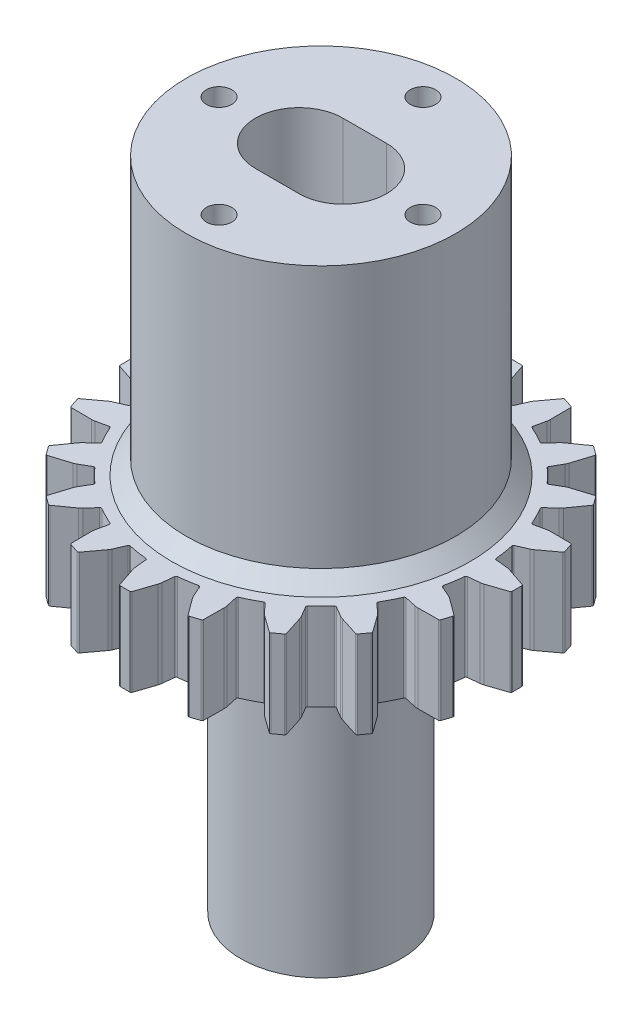
SolidWorks part; units mm, degrees
ref_plane "Front Plane" through (0, 0, 0) normal (0, 0, 1) x (1, 0, 0)
ref_plane "Top Plane" through (0, 0, 0) normal (0, 1, 0) x (1, 0, 0)
ref_plane "Right Plane" through (0, 0, 0) normal (1, 0, 0) x (0, 0, -1)
sketch "Sketch1" plane through (0, 0, 0) normal (0, 1, 0) x (1, 0, 0)
  line L0 (0, 23.8701) -> (0, -17.0658) construction
  line L1 (-0.9918, 11.0363) -> (-0.9111, 11.8435)
  line L2 (-0.8647, 12.0602) -> (-0.4228, 13.3861)
  line L3 (-0.3279, 13.4545) -> (0.3279, 13.4545)
  line L4 (0.4228, 13.3861) -> (0.8647, 12.0602)
  line L5 (0.9111, 11.8435) -> (0.9918, 11.0363)
  line L6 (2.4671, 10.8026) -> (2.7933, 11.5454)
  line L7 (2.9044, 11.7372) -> (3.7344, 12.8616)
  line L8 (3.8458, 12.8973) -> (4.4695, 12.6946)
  line L9 (4.5386, 12.6003) -> (4.5492, 11.2027)
  line L10 (4.5263, 10.9823) -> (4.3537, 10.1896)
  line L11 (5.6846, 9.5115) -> (6.2243, 10.1171)
  line L12 (6.3892, 10.2652) -> (7.5261, 11.0781)
  line L13 (7.643, 11.0776) -> (8.1736, 10.6921)
  line L14 (8.2102, 10.5811) -> (7.7884, 9.2486)
  line L15 (7.6985, 9.0461) -> (7.2894, 8.3456)
  line L16 (8.3456, 7.2894) -> (9.0461, 7.6985)
  line L17 (9.2486, 7.7884) -> (10.5811, 8.2102)
  line L18 (10.6921, 8.1736) -> (11.0776, 7.643)
  line L19 (11.0781, 7.5261) -> (10.2652, 6.3892)
  line L20 (10.1171, 6.2243) -> (9.5115, 5.6846)
  line L21 (10.1896, 4.3537) -> (10.9823, 4.5263)
  line L22 (11.2027, 4.5492) -> (12.6003, 4.5386)
  line L23 (12.6946, 4.4695) -> (12.8973, 3.8458)
  line L24 (12.8616, 3.7344) -> (11.7372, 2.9044)
  line L25 (11.5454, 2.7933) -> (10.8026, 2.4671)
  line L26 (11.0363, 0.9918) -> (11.8435, 0.9111)
  line L27 (12.0602, 0.8647) -> (13.3861, 0.4228)
  line L28 (13.4545, 0.3279) -> (13.4545, -0.3279)
  line L29 (13.3861, -0.4228) -> (12.0602, -0.8647)
  line L30 (11.8435, -0.9111) -> (11.0363, -0.9918)
  line L31 (10.8026, -2.4671) -> (11.5454, -2.7933)
  line L32 (11.7372, -2.9044) -> (12.8616, -3.7344)
  line L33 (12.8973, -3.8458) -> (12.6946, -4.4695)
  line L34 (12.6003, -4.5386) -> (11.2027, -4.5492)
  line L35 (10.9823, -4.5263) -> (10.1896, -4.3537)
  line L36 (9.5115, -5.6846) -> (10.1171, -6.2243)
  line L37 (10.2652, -6.3892) -> (11.0781, -7.5261)
  line L38 (11.0776, -7.643) -> (10.6921, -8.1736)
  line L39 (10.5811, -8.2102) -> (9.2486, -7.7884)
  line L40 (9.0461, -7.6985) -> (8.3456, -7.2894)
  line L41 (7.2894, -8.3456) -> (7.6985, -9.0461)
  line L42 (7.7884, -9.2486) -> (8.2102, -10.5811)
  line L43 (8.1736, -10.6921) -> (7.643, -11.0776)
  line L44 (7.5261, -11.0781) -> (6.3892, -10.2652)
  line L45 (6.2243, -10.1171) -> (5.6846, -9.5115)
  line L46 (4.3537, -10.1896) -> (4.5263, -10.9823)
  line L47 (4.5492, -11.2027) -> (4.5386, -12.6003)
  line L48 (4.4695, -12.6946) -> (3.8458, -12.8973)
  line L49 (3.7344, -12.8616) -> (2.9044, -11.7372)
  line L50 (2.7933, -11.5454) -> (2.4671, -10.8026)
  line L51 (0.9918, -11.0363) -> (0.9111, -11.8435)
  line L52 (0.8647, -12.0602) -> (0.4228, -13.3861)
  line L53 (0.3279, -13.4545) -> (-0.3279, -13.4545)
  line L54 (-0.4228, -13.3861) -> (-0.8647, -12.0602)
  line L55 (-0.9111, -11.8435) -> (-0.9918, -11.0363)
  line L56 (-2.4671, -10.8026) -> (-2.7933, -11.5454)
  line L57 (-2.9044, -11.7372) -> (-3.7344, -12.8616)
  line L58 (-3.8458, -12.8973) -> (-4.4695, -12.6946)
  line L59 (-4.5386, -12.6003) -> (-4.5492, -11.2027)
  line L60 (-4.5263, -10.9823) -> (-4.3537, -10.1896)
  line L61 (-5.6846, -9.5115) -> (-6.2243, -10.1171)
  line L62 (-6.3892, -10.2652) -> (-7.5261, -11.0781)
  line L63 (-7.643, -11.0776) -> (-8.1736, -10.6921)
  line L64 (-8.2102, -10.5811) -> (-7.7884, -9.2486)
  line L65 (-7.6985, -9.0461) -> (-7.2894, -8.3456)
  line L66 (-8.3456, -7.2894) -> (-9.0461, -7.6985)
  line L67 (-9.2486, -7.7884) -> (-10.5811, -8.2102)
  line L68 (-10.6921, -8.1736) -> (-11.0776, -7.643)
  line L69 (-11.0781, -7.5261) -> (-10.2652, -6.3892)
  line L70 (-10.1171, -6.2243) -> (-9.5115, -5.6846)
  line L71 (-10.1896, -4.3537) -> (-10.9823, -4.5263)
  line L72 (-11.2027, -4.5492) -> (-12.6003, -4.5386)
  line L73 (-12.6946, -4.4695) -> (-12.8973, -3.8458)
  line L74 (-12.8616, -3.7344) -> (-11.7372, -2.9044)
  line L75 (-11.5454, -2.7933) -> (-10.8026, -2.4671)
  line L76 (-11.0363, -0.9918) -> (-11.8435, -0.9111)
  line L77 (-12.0602, -0.8647) -> (-13.3861, -0.4228)
  line L78 (-13.4545, -0.3279) -> (-13.4545, 0.3279)
  line L79 (-13.3861, 0.4228) -> (-12.0602, 0.8647)
  line L80 (-11.8435, 0.9111) -> (-11.0363, 0.9918)
  line L81 (-10.8026, 2.4671) -> (-11.5454, 2.7933)
  line L82 (-11.7372, 2.9044) -> (-12.8616, 3.7344)
  line L83 (-12.8973, 3.8458) -> (-12.6946, 4.4695)
  line L84 (-12.6003, 4.5386) -> (-11.2027, 4.5492)
  line L85 (-10.9823, 4.5263) -> (-10.1896, 4.3537)
  line L86 (-9.5115, 5.6846) -> (-10.1171, 6.2243)
  line L87 (-10.2652, 6.3892) -> (-11.0781, 7.5261)
  line L88 (-11.0776, 7.643) -> (-10.6921, 8.1736)
  line L89 (-10.5811, 8.2102) -> (-9.2486, 7.7884)
  line L90 (-9.0461, 7.6985) -> (-8.3456, 7.2894)
  line L91 (-7.2894, 8.3456) -> (-7.6985, 9.0461)
  line L92 (-7.7884, 9.2486) -> (-8.2102, 10.5811)
  line L93 (-8.1736, 10.6921) -> (-7.643, 11.0776)
  line L94 (-7.5261, 11.0781) -> (-6.3892, 10.2652)
  line L95 (-6.2243, 10.1171) -> (-5.6846, 9.5115)
  line L96 (-4.3537, 10.1896) -> (-4.5263, 10.9823)
  line L97 (-4.5492, 11.2027) -> (-4.5386, 12.6003)
  line L98 (-4.4695, 12.6946) -> (-3.8458, 12.8973)
  line L99 (-3.7344, 12.8616) -> (-2.9044, 11.7372)
  line L100 (-2.7933, 11.5454) -> (-2.4671, 10.8026)
  arc A0 (-1.0815, 10.9467) -> (-2.3542, 10.7451) centre (0, 0) ccw
  arc A1 (0.8647, 12.0602) -> (0.9111, 11.8435) centre (-0.0839, 11.744) cw
  arc A2 (-0.9111, 11.8435) -> (-0.8647, 12.0602) centre (0.0839, 11.744) cw
  arc A3 (0.3279, 13.4545) -> (0.4228, 13.3861) centre (0.3279, 13.3545) cw
  arc A4 (-0.4228, 13.3861) -> (-0.3279, 13.4545) centre (-0.3279, 13.3545) cw
  arc A5 (0.9918, 11.0363) -> (1.0815, 10.9467) centre (1.0913, 11.0462) ccw
  arc A6 (-0.9918, 11.0363) -> (-1.0815, 10.9467) centre (-1.0913, 11.0462) cw
  arc A7 (2.4671, 10.8026) -> (2.3542, 10.7451) centre (2.3756, 10.8428) cw
  arc A8 (2.7933, 11.5454) -> (2.9044, 11.7372) centre (3.7089, 11.1433) cw
  arc A9 (3.7344, 12.8616) -> (3.8458, 12.8973) centre (3.8149, 12.8022) cw
  arc A10 (4.4695, 12.6946) -> (4.5386, 12.6003) centre (4.4386, 12.5995) cw
  arc A11 (4.5492, 11.2027) -> (4.5263, 10.9823) centre (3.5493, 11.1951) cw
  arc A12 (4.3537, 10.1896) -> (4.4113, 10.0767) centre (4.4514, 10.1683) ccw
  arc A13 (5.6846, 9.5115) -> (5.5594, 9.4918) centre (5.6099, 9.578) cw
  arc A14 (6.2243, 10.1171) -> (6.3892, 10.2652) centre (6.9709, 9.4518) cw
  arc A15 (7.5261, 11.0781) -> (7.643, 11.0776) centre (7.5843, 10.9967) cw
  arc A16 (8.1736, 10.6921) -> (8.2102, 10.5811) centre (8.1148, 10.6112) cw
  arc A17 (7.7884, 9.2486) -> (7.6985, 9.0461) centre (6.835, 9.5504) cw
  arc A18 (7.2894, 8.3456) -> (7.3093, 8.2204) centre (7.3757, 8.2951) ccw
  arc A19 (8.3456, 7.2894) -> (8.2204, 7.3093) centre (8.2951, 7.3757) cw
  arc A20 (9.0461, 7.6985) -> (9.2486, 7.7884) centre (9.5504, 6.835) cw
  arc A21 (10.5811, 8.2102) -> (10.6921, 8.1736) centre (10.6112, 8.1148) cw
  arc A22 (11.0776, 7.643) -> (11.0781, 7.5261) centre (10.9967, 7.5843) cw
  arc A23 (10.2652, 6.3892) -> (10.1171, 6.2243) centre (9.4518, 6.9709) cw
  arc A24 (9.5115, 5.6846) -> (9.4918, 5.5594) centre (9.578, 5.6099) ccw
  arc A25 (10.1896, 4.3537) -> (10.0767, 4.4113) centre (10.1683, 4.4514) cw
  arc A26 (10.9823, 4.5263) -> (11.2027, 4.5492) centre (11.1951, 3.5493) cw
  arc A27 (12.6003, 4.5386) -> (12.6946, 4.4695) centre (12.5995, 4.4386) cw
  arc A28 (12.8973, 3.8458) -> (12.8616, 3.7344) centre (12.8022, 3.8149) cw
  arc A29 (11.7372, 2.9044) -> (11.5454, 2.7933) centre (11.1433, 3.7089) cw
  arc A30 (10.8026, 2.4671) -> (10.7451, 2.3542) centre (10.8428, 2.3756) ccw
  arc A31 (11.0363, 0.9918) -> (10.9467, 1.0815) centre (11.0462, 1.0913) cw
  arc A32 (11.8435, 0.9111) -> (12.0602, 0.8647) centre (11.744, -0.0839) cw
  arc A33 (13.3861, 0.4228) -> (13.4545, 0.3279) centre (13.3545, 0.3279) cw
  arc A34 (13.4545, -0.3279) -> (13.3861, -0.4228) centre (13.3545, -0.3279) cw
  arc A35 (12.0602, -0.8647) -> (11.8435, -0.9111) centre (11.744, 0.0839) cw
  arc A36 (11.0363, -0.9918) -> (10.9467, -1.0815) centre (11.0462, -1.0913) ccw
  arc A37 (10.8026, -2.4671) -> (10.7451, -2.3542) centre (10.8428, -2.3756) cw
  arc A38 (11.5454, -2.7933) -> (11.7372, -2.9044) centre (11.1433, -3.7089) cw
  arc A39 (12.8616, -3.7344) -> (12.8973, -3.8458) centre (12.8022, -3.8149) cw
  arc A40 (12.6946, -4.4695) -> (12.6003, -4.5386) centre (12.5995, -4.4386) cw
  arc A41 (11.2027, -4.5492) -> (10.9823, -4.5263) centre (11.1951, -3.5493) cw
  arc A42 (10.1896, -4.3537) -> (10.0767, -4.4113) centre (10.1683, -4.4514) ccw
  arc A43 (9.5115, -5.6846) -> (9.4918, -5.5594) centre (9.578, -5.6099) cw
  arc A44 (10.1171, -6.2243) -> (10.2652, -6.3892) centre (9.4518, -6.9709) cw
  arc A45 (11.0781, -7.5261) -> (11.0776, -7.643) centre (10.9967, -7.5843) cw
  arc A46 (10.6921, -8.1736) -> (10.5811, -8.2102) centre (10.6112, -8.1148) cw
  arc A47 (9.2486, -7.7884) -> (9.0461, -7.6985) centre (9.5504, -6.835) cw
  arc A48 (8.3456, -7.2894) -> (8.2204, -7.3093) centre (8.2951, -7.3757) ccw
  arc A49 (7.2894, -8.3456) -> (7.3093, -8.2204) centre (7.3757, -8.2951) cw
  arc A50 (7.6985, -9.0461) -> (7.7884, -9.2486) centre (6.835, -9.5504) cw
  arc A51 (8.2102, -10.5811) -> (8.1736, -10.6921) centre (8.1148, -10.6112) cw
  arc A52 (7.643, -11.0776) -> (7.5261, -11.0781) centre (7.5843, -10.9967) cw
  arc A53 (6.3892, -10.2652) -> (6.2243, -10.1171) centre (6.9709, -9.4518) cw
  arc A54 (5.6846, -9.5115) -> (5.5594, -9.4918) centre (5.6099, -9.578) ccw
  arc A55 (4.3537, -10.1896) -> (4.4113, -10.0767) centre (4.4514, -10.1683) cw
  arc A56 (4.5263, -10.9823) -> (4.5492, -11.2027) centre (3.5493, -11.1951) cw
  arc A57 (4.5386, -12.6003) -> (4.4695, -12.6946) centre (4.4386, -12.5995) cw
  arc A58 (3.8458, -12.8973) -> (3.7344, -12.8616) centre (3.8149, -12.8022) cw
  arc A59 (2.9044, -11.7372) -> (2.7933, -11.5454) centre (3.7089, -11.1433) cw
  arc A60 (2.4671, -10.8026) -> (2.3542, -10.7451) centre (2.3756, -10.8428) ccw
  arc A61 (0.9918, -11.0363) -> (1.0815, -10.9467) centre (1.0913, -11.0462) cw
  arc A62 (0.9111, -11.8435) -> (0.8647, -12.0602) centre (-0.0839, -11.744) cw
  arc A63 (0.4228, -13.3861) -> (0.3279, -13.4545) centre (0.3279, -13.3545) cw
  arc A64 (-0.3279, -13.4545) -> (-0.4228, -13.3861) centre (-0.3279, -13.3545) cw
  arc A65 (-0.8647, -12.0602) -> (-0.9111, -11.8435) centre (0.0839, -11.744) cw
  arc A66 (-0.9918, -11.0363) -> (-1.0815, -10.9467) centre (-1.0913, -11.0462) ccw
  arc A67 (-2.4671, -10.8026) -> (-2.3542, -10.7451) centre (-2.3756, -10.8428) cw
  arc A68 (-2.7933, -11.5454) -> (-2.9044, -11.7372) centre (-3.7089, -11.1433) cw
  arc A69 (-3.7344, -12.8616) -> (-3.8458, -12.8973) centre (-3.8149, -12.8022) cw
  arc A70 (-4.4695, -12.6946) -> (-4.5386, -12.6003) centre (-4.4386, -12.5995) cw
  arc A71 (-4.5492, -11.2027) -> (-4.5263, -10.9823) centre (-3.5493, -11.1951) cw
  arc A72 (-4.3537, -10.1896) -> (-4.4113, -10.0767) centre (-4.4514, -10.1683) ccw
  arc A73 (-5.6846, -9.5115) -> (-5.5594, -9.4918) centre (-5.6099, -9.578) cw
  arc A74 (-6.2243, -10.1171) -> (-6.3892, -10.2652) centre (-6.9709, -9.4518) cw
  arc A75 (-7.5261, -11.0781) -> (-7.643, -11.0776) centre (-7.5843, -10.9967) cw
  arc A76 (-8.1736, -10.6921) -> (-8.2102, -10.5811) centre (-8.1148, -10.6112) cw
  arc A77 (-7.7884, -9.2486) -> (-7.6985, -9.0461) centre (-6.835, -9.5504) cw
  arc A78 (-7.2894, -8.3456) -> (-7.3093, -8.2204) centre (-7.3757, -8.2951) ccw
  arc A79 (-8.3456, -7.2894) -> (-8.2204, -7.3093) centre (-8.2951, -7.3757) cw
  arc A80 (-9.0461, -7.6985) -> (-9.2486, -7.7884) centre (-9.5504, -6.835) cw
  arc A81 (-10.5811, -8.2102) -> (-10.6921, -8.1736) centre (-10.6112, -8.1148) cw
  arc A82 (-11.0776, -7.643) -> (-11.0781, -7.5261) centre (-10.9967, -7.5843) cw
  arc A83 (-10.2652, -6.3892) -> (-10.1171, -6.2243) centre (-9.4518, -6.9709) cw
  arc A84 (-9.5115, -5.6846) -> (-9.4918, -5.5594) centre (-9.578, -5.6099) ccw
  arc A85 (-10.1896, -4.3537) -> (-10.0767, -4.4113) centre (-10.1683, -4.4514) cw
  arc A86 (-10.9823, -4.5263) -> (-11.2027, -4.5492) centre (-11.1951, -3.5493) cw
  arc A87 (-12.6003, -4.5386) -> (-12.6946, -4.4695) centre (-12.5995, -4.4386) cw
  arc A88 (-12.8973, -3.8458) -> (-12.8616, -3.7344) centre (-12.8022, -3.8149) cw
  arc A89 (-11.7372, -2.9044) -> (-11.5454, -2.7933) centre (-11.1433, -3.7089) cw
  arc A90 (-10.8026, -2.4671) -> (-10.7451, -2.3542) centre (-10.8428, -2.3756) ccw
  arc A91 (-11.0363, -0.9918) -> (-10.9467, -1.0815) centre (-11.0462, -1.0913) cw
  arc A92 (-11.8435, -0.9111) -> (-12.0602, -0.8647) centre (-11.744, 0.0839) cw
  arc A93 (-13.3861, -0.4228) -> (-13.4545, -0.3279) centre (-13.3545, -0.3279) cw
  arc A94 (-13.4545, 0.3279) -> (-13.3861, 0.4228) centre (-13.3545, 0.3279) cw
  arc A95 (-12.0602, 0.8647) -> (-11.8435, 0.9111) centre (-11.744, -0.0839) cw
  arc A96 (-11.0363, 0.9918) -> (-10.9467, 1.0815) centre (-11.0462, 1.0913) ccw
  arc A97 (-10.8026, 2.4671) -> (-10.7451, 2.3542) centre (-10.8428, 2.3756) cw
  arc A98 (-11.5454, 2.7933) -> (-11.7372, 2.9044) centre (-11.1433, 3.7089) cw
  arc A99 (-12.8616, 3.7344) -> (-12.8973, 3.8458) centre (-12.8022, 3.8149) cw
  arc A100 (-12.6946, 4.4695) -> (-12.6003, 4.5386) centre (-12.5995, 4.4386) cw
  arc A101 (-11.2027, 4.5492) -> (-10.9823, 4.5263) centre (-11.1951, 3.5493) cw
  arc A102 (-10.1896, 4.3537) -> (-10.0767, 4.4113) centre (-10.1683, 4.4514) ccw
  arc A103 (-9.5115, 5.6846) -> (-9.4918, 5.5594) centre (-9.578, 5.6099) cw
  arc A104 (-10.1171, 6.2243) -> (-10.2652, 6.3892) centre (-9.4518, 6.9709) cw
  arc A105 (-11.0781, 7.5261) -> (-11.0776, 7.643) centre (-10.9967, 7.5843) cw
  arc A106 (-10.6921, 8.1736) -> (-10.5811, 8.2102) centre (-10.6112, 8.1148) cw
  arc A107 (-9.2486, 7.7884) -> (-9.0461, 7.6985) centre (-9.5504, 6.835) cw
  arc A108 (-8.3456, 7.2894) -> (-8.2204, 7.3093) centre (-8.2951, 7.3757) ccw
  arc A109 (-7.2894, 8.3456) -> (-7.3093, 8.2204) centre (-7.3757, 8.2951) cw
  arc A110 (-7.6985, 9.0461) -> (-7.7884, 9.2486) centre (-6.835, 9.5504) cw
  arc A111 (-8.2102, 10.5811) -> (-8.1736, 10.6921) centre (-8.1148, 10.6112) cw
  arc A112 (-7.643, 11.0776) -> (-7.5261, 11.0781) centre (-7.5843, 10.9967) cw
  arc A113 (-6.3892, 10.2652) -> (-6.2243, 10.1171) centre (-6.9709, 9.4518) cw
  arc A114 (-5.6846, 9.5115) -> (-5.5594, 9.4918) centre (-5.6099, 9.578) ccw
  arc A115 (-4.3537, 10.1896) -> (-4.4113, 10.0767) centre (-4.4514, 10.1683) cw
  arc A116 (-4.5263, 10.9823) -> (-4.5492, 11.2027) centre (-3.5493, 11.1951) cw
  arc A117 (-4.5386, 12.6003) -> (-4.4695, 12.6946) centre (-4.4386, 12.5995) cw
  arc A118 (-3.8458, 12.8973) -> (-3.7344, 12.8616) centre (-3.8149, 12.8022) cw
  arc A119 (-2.9044, 11.7372) -> (-2.7933, 11.5454) centre (-3.7089, 11.1433) cw
  arc A120 (-2.4671, 10.8026) -> (-2.3542, 10.7451) centre (-2.3756, 10.8428) ccw
  arc A121 (-4.4113, 10.0767) -> (-5.5594, 9.4918) centre (0, 0) ccw
  arc A122 (-7.3093, 8.2204) -> (-8.2204, 7.3093) centre (0, 0) ccw
  arc A123 (-9.4918, 5.5594) -> (-10.0767, 4.4113) centre (0, 0) ccw
  arc A124 (-10.7451, 2.3542) -> (-10.9467, 1.0815) centre (0, 0) ccw
  arc A125 (-10.0767, -4.4113) -> (-9.4918, -5.5594) centre (0, 0) ccw
  arc A126 (-8.2204, -7.3093) -> (-7.3093, -8.2204) centre (0, 0) ccw
  arc A127 (-5.5594, -9.4918) -> (-4.4113, -10.0767) centre (0, 0) ccw
  arc A128 (-2.3542, -10.7451) -> (-1.0815, -10.9467) centre (0, 0) ccw
  arc A129 (1.0815, -10.9467) -> (2.3542, -10.7451) centre (0, 0) ccw
  arc A130 (4.4113, -10.0767) -> (5.5594, -9.4918) centre (0, 0) ccw
  arc A131 (7.3093, -8.2204) -> (8.2204, -7.3093) centre (0, 0) ccw
  arc A132 (9.4918, -5.5594) -> (10.0767, -4.4113) centre (0, 0) ccw
  arc A133 (10.7451, -2.3542) -> (10.9467, -1.0815) centre (0, 0) ccw
  arc A134 (10.9467, 1.0815) -> (10.7451, 2.3542) centre (0, 0) ccw
  arc A135 (10.0767, 4.4113) -> (9.4918, 5.5594) centre (0, 0) ccw
  arc A136 (8.2204, 7.3093) -> (7.3093, 8.2204) centre (0, 0) ccw
  arc A137 (5.5594, 9.4918) -> (4.4113, 10.0767) centre (0, 0) ccw
  arc A138 (2.3542, 10.7451) -> (1.0815, 10.9467) centre (0, 0) ccw
  arc A139 (-10.9467, -1.0815) -> (-10.7451, -2.3542) centre (0, 0) ccw
  point P7 (0, 13.4545)
  point P12 (0, 11)
  point P21 (0.9, 11.9545)
  point P24 (-0.9, 11.9545)
  point P27 (0.4, 13.4545)
  point P30 (-0.4, 13.4545)
  point P32 (1, 10.9545)
  point P35 (-1, 10.9545)
  point P374 (0, 0)
  dimension "D1" = 22
  dimension "D9" = 1
  dimension "D10" = 0.1
  dimension "D11" = 0.1
  dimension "D2" = 0.8
  dimension "D3" = 1
  dimension "D4" = 2.5
  dimension "D5" = 1
  dimension "D6" = 2
  dimension "D7" = 0.1
  dimension "D8" = 0.1
  dimension "D12" = 20
extrude "Boss-Extrude1" add sketch "Sketch1" along normal blind 6
sketch "Sketch2" plane through (0, 0, 0) normal (0, -1, 0) x (1, 0, 0)
  circle A0 centre (0, 0) radius 8.5
  circle A1 centre (0, 0) radius 5.5
  dimension "D1" = 17
  dimension "D2" = 11
extrude "Cut-Extrude1" cut sketch "Sketch2" against normal blind 4.5
sketch "Sketch3" plane through (0, 6, 0) normal (0, 1, 0) x (1, 0, 0)
  circle A0 centre (0, 0) radius 9.25
  dimension "D1" = 18.5
extrude "Boss-Extrude2" add sketch "Sketch3" along normal blind 19
sketch "Sketch4" plane through (0, 25, 0) normal (0, 1, 0) x (1, 0, 0)
  circle A0 centre (0, 7) radius 0.875
  circle A4 centre (7, 0) radius 0.875
  circle A7 centre (0, -7) radius 0.875
  circle A10 centre (-7, 0) radius 0.875
  point P27 (0, 0)
  dimension "D1" = 7
  dimension "D3" = 4
extrude "Cut-Extrude2" cut sketch "Sketch4" against normal blind 15
sketch "Sketch6" plane through (0, 25, 0) normal (0, 1, 0) x (1, 0, 0)
  line L0 (-18.0612, 0) -> (18.3147, 0) construction
  line L1 (0, 13.2248) -> (0, -13.8666) construction
  circle A0 centre (0.1267, 0) radius 2.1107
  point P5 (0, 0)
ref_point "Point1"
ref_plane "Plane1" through (0, -20, 0) normal (0, -1, 0) x (-1, 0, 0)
sketch "Sketch7" plane through (0, 0, 0) normal (0, -1, 0) x (1, 0, 0)
  circle A3 centre (0, 0) radius 5.5
  dimension "D1" = 11
sketch "Sketch8" plane through (0, -20, 0) normal (0, -1, 0) x (-1, 0, 0)
  circle A0 centre (0, 0) radius 5.5
  dimension "D1" = 11
loft "Loft1" add profiles "Sketch7", "Sketch8"
sketch "Sketch5" plane through (0, 0, 0) normal (0, -1, 0) x (1, 0, 0)
  line L0 (-1.5, 3) -> (1.5, 3)
  line L1 (-1.5, -3) -> (1.5, -3)
  line L2 (-1.5, 0) -> (1.5, 0) construction
  arc A0 (-1.5, 3) -> (-1.5, -3) centre (-1.5, 0) ccw
  arc A1 (1.5, -3) -> (1.5, 3) centre (1.5, 0) ccw
  point P6 (0, 0)
  dimension "D2" = 3
  dimension "D1" = 3
extrude "Cut-Extrude5" cut sketch "Sketch5" along direction (0, 1, 0) on the side against the normal through all both and the other way through all
chamfer "Chamfer2" distance 1 angle 45 1 edges at (0, 6, 9.25)
